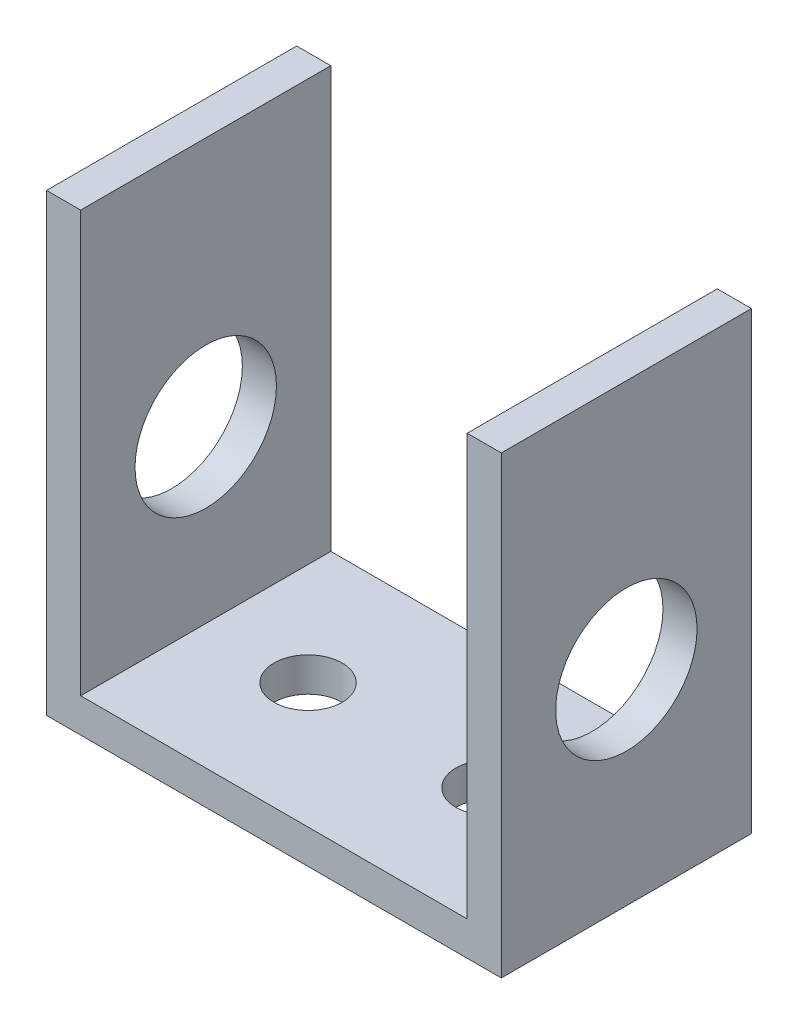
SolidWorks part; units mm, degrees
ref_plane "Plan de face" through (0, 0, 0) normal (0, 0, 1) x (1, 0, 0)
ref_plane "Plan de dessus" through (0, 0, 0) normal (0, 1, 0) x (1, 0, 0)
ref_plane "Plan de droite" through (0, 0, 0) normal (1, 0, 0) x (0, 0, -1)
sketch "Esquisse1" plane through (0, 0, 0) normal (0, 0, 1) x (1, 0, 0)
  line L0 (-11.0948, -6.6863) -> (-11.0948, 13.3137)
  line L1 (-11.0948, 13.3137) -> (-9.5948, 13.3137)
  line L2 (-11.0948, -6.6863) -> (8.9052, -6.6863)
  line L3 (8.9052, -6.6863) -> (8.9052, 13.3137)
  line L4 (8.9052, 13.3137) -> (7.4052, 13.3137)
  line L5 (-9.5948, 13.3137) -> (-9.5948, -5.1863)
  line L6 (7.4052, 13.3137) -> (7.4052, -5.1863)
  line L7 (7.4052, -5.1863) -> (-9.5948, -5.1863)
  dimension "D1" = 1.5
  dimension "D2" = 20
  dimension "D3" = 1.5
  dimension "D4" = 1.5
  dimension "D5" = 20
  dimension "D6" = 20
extrude "Extrusion1" add sketch "Esquisse1" along normal blind 11
sketch "Esquisse2" plane through (8.9052, 0, 0) normal (1, 0, 0) x (0, 0, -1)
  line L0 (0, -6.6863) -> (0, 13.3137) construction
  line L2 (-11, -6.6863) -> (0, -6.6863) construction
  circle A0 centre (-5.5, 2.3137) radius 3.11
  dimension "D1" = 5.5
  dimension "D2" = 9
extrude "Extrusion2" cut sketch "Esquisse2" against normal through all
sketch "Esquisse3" plane through (0, -5.1863, 0) normal (0, 1, 0) x (-1, 0, 0)
  line L0 (-7.4052, 0) -> (9.5948, 0) construction
  line L1 (9.5948, 11) -> (9.5948, 0) construction
  line L2 (-7.4052, 11) -> (-7.4052, 0) construction
  circle A0 centre (5.0948, 5.5) radius 1.5
  circle A1 centre (-2.9052, 5.5) radius 1.5
  point P6 (9.5948, 5.5)
  dimension "D1" = 5.5
  dimension "D2" = 5.5
  dimension "D3" = 4.5
  dimension "D4" = 4.5
extrude "Extrusion3" cut sketch "Esquisse3" against normal blind 11
